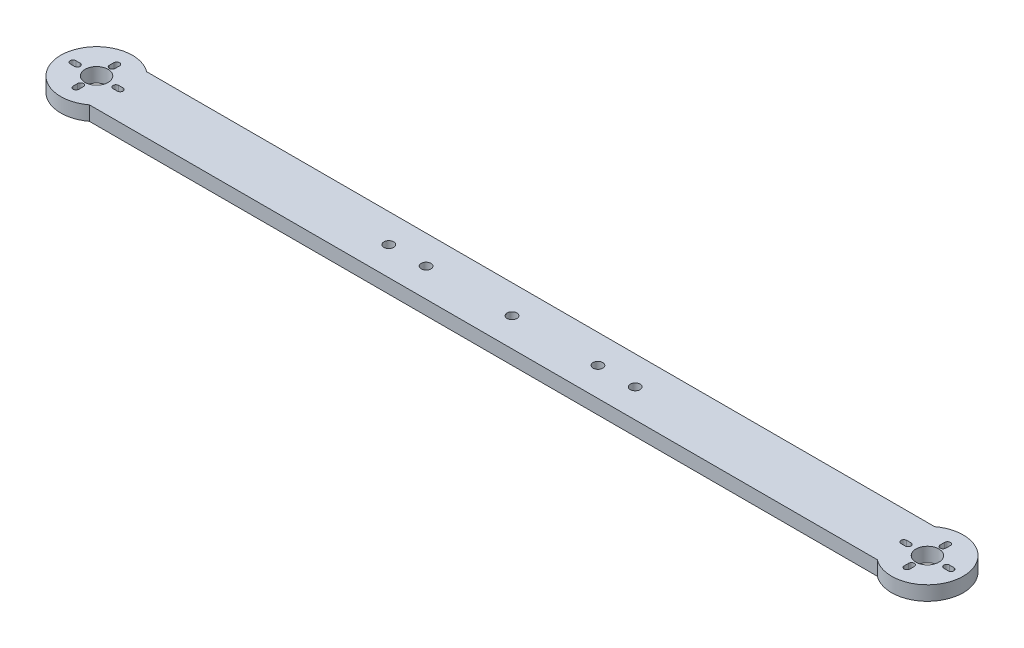
SolidWorks part; units mm, degrees
ref_plane "Front Plane" through (0, 0, 0) normal (0, 0, 1) x (1, 0, 0)
ref_plane "Top Plane" through (0, 0, 0) normal (0, 1, 0) x (1, 0, 0)
ref_plane "Right Plane" through (0, 0, 0) normal (1, 0, 0) x (0, 0, -1)
sketch "Sketch1" plane through (0, 0, 0) normal (0, 1, 0) x (1, 0, 0)
  line L0 (0, 12.7) -> (0, -12.7) construction
  line L1 (-174.625, 12.7) -> (174.625, 12.7)
  line L3 (-174.625, -12.7) -> (174.625, -12.7)
  arc A0 (-174.625, 12.7) -> (-174.625, -12.7) centre (-184.15, 0) ccw
  arc A1 (174.625, -12.7) -> (174.625, 12.7) centre (184.15, 0) ccw
  point P8 (0, 12.7)
  point P12 (0, 0)
  dimension "D3" = 31.75
  dimension "D4" = 31.75
extrude "Boss-Extrude1" add sketch "Sketch1" along normal blind 6.35
sketch "Sketch2" plane through (0, 6.35, 0) normal (0, 1, 0) x (1, 0, 0)
  line L0 (173.6914, 0) -> (175.6086, 0) construction
  line L1 (173.6914, 1.25) -> (175.6086, 1.25)
  line L2 (173.6914, -1.25) -> (175.6086, -1.25)
  line L3 (184.15, 0) -> (184.15, 3.2374) construction
  line L4 (194.6086, 0) -> (192.6914, 0) construction
  line L5 (194.6086, 1.25) -> (192.6914, 1.25)
  line L6 (194.6086, -1.25) -> (192.6914, -1.25)
  line L7 (184.15, 8.9209) -> (184.15, 6.921) construction
  line L8 (185.4, 8.9209) -> (185.4, 6.921)
  line L9 (182.9, 8.9209) -> (182.9, 6.921)
  line L10 (184.1914, -9.079) -> (184.1914, -7.079) construction
  line L11 (185.4414, -9.079) -> (185.4414, -7.079)
  line L12 (182.9414, -9.079) -> (182.9414, -7.079)
  line L13 (0, 0) -> (184.15, 0) construction
  line L14 (0, 0) -> (0, 12.7) construction
  line L15 (174.625, 12.7) -> (-174.625, 12.7) construction
  line L16 (-184.15, 0) -> (-184.15, 3.2374) construction
  line L17 (-184.1914, -9.079) -> (-184.1914, -7.079) construction
  line L18 (-185.4414, -9.079) -> (-185.4414, -7.079)
  line L19 (-182.9414, -9.079) -> (-182.9414, -7.079)
  line L20 (-184.15, 8.9209) -> (-184.15, 6.921) construction
  line L21 (-185.4, 8.9209) -> (-185.4, 6.921)
  line L22 (-182.9, 8.9209) -> (-182.9, 6.921)
  line L23 (-194.6086, 0) -> (-192.6914, 0) construction
  line L24 (-194.6086, 1.25) -> (-192.6914, 1.25)
  line L25 (-194.6086, -1.25) -> (-192.6914, -1.25)
  line L26 (-173.6914, 0) -> (-175.6086, 0) construction
  line L27 (-173.6914, 1.25) -> (-175.6086, 1.25)
  line L28 (-173.6914, -1.25) -> (-175.6086, -1.25)
  circle A0 centre (184.15, 0) radius 5.08
  arc A1 (173.6914, 1.25) -> (173.6914, -1.25) centre (173.6914, 0) ccw
  arc A2 (175.6086, -1.25) -> (175.6086, 1.25) centre (175.6086, 0) ccw
  arc A3 (194.6086, 1.25) -> (194.6086, -1.25) centre (194.6086, 0) cw
  arc A4 (192.6914, -1.25) -> (192.6914, 1.25) centre (192.6914, 0) cw
  arc A5 (185.4, 8.9209) -> (182.9, 8.9209) centre (184.15, 8.9209) ccw
  arc A6 (182.9, 6.921) -> (185.4, 6.921) centre (184.15, 6.921) ccw
  arc A7 (185.4414, -9.079) -> (182.9414, -9.079) centre (184.1914, -9.079) cw
  arc A8 (182.9414, -7.079) -> (185.4414, -7.079) centre (184.1914, -7.079) cw
  circle A9 centre (-184.15, 0) radius 5.08
  arc A10 (-185.4414, -9.079) -> (-182.9414, -9.079) centre (-184.1914, -9.079) ccw
  arc A11 (-182.9414, -7.079) -> (-185.4414, -7.079) centre (-184.1914, -7.079) ccw
  arc A12 (-185.4, 8.9209) -> (-182.9, 8.9209) centre (-184.15, 8.9209) cw
  arc A13 (-182.9, 6.921) -> (-185.4, 6.921) centre (-184.15, 6.921) cw
  arc A14 (-194.6086, 1.25) -> (-194.6086, -1.25) centre (-194.6086, 0) ccw
  arc A15 (-192.6914, -1.25) -> (-192.6914, 1.25) centre (-192.6914, 0) ccw
  arc A16 (-173.6914, 1.25) -> (-173.6914, -1.25) centre (-173.6914, 0) cw
  arc A17 (-175.6086, -1.25) -> (-175.6086, 1.25) centre (-175.6086, 0) cw
  point P4 (174.65, 0)
  point P12 (193.65, 0)
  point P19 (184.15, 7.921)
  point P26 (184.1914, -8.079)
  point P41 (-184.1914, -8.079)
  point P48 (-184.15, 7.921)
  point P55 (-193.65, 0)
  point P62 (-174.65, 0)
  dimension "D4" = 10.16
  dimension "D1" = 16
  dimension "D2" = 19
  dimension "D3" = 184.15
  dimension "D5" = 1.9999
extrude "Cut-Extrude1" cut sketch "Sketch2" against normal through all
sketch "Sketch3" plane through (0, 6.35, 0) normal (0, 1, 0) x (1, 0, 0)
  circle A0 centre (0, 0) radius 2.159
  circle A1 centre (38.1, 0) radius 2.159
  circle A2 centre (-38.1, 0) radius 2.159
  dimension "D1" = 38.1
  dimension "D3" = 4.318
  dimension "D4" = 4.318
  dimension "D5" = 4.318
  dimension "D2" = 38.1
extrude "Cut-Extrude2" cut sketch "Sketch3" against normal through all
ref_plane "Plane1" through (-174.625, 0, 12.7) normal (1, 0, 0) x (0, 0, -1)
sketch "Sketch6" plane through (0, 0, 0) normal (0, -1, 0) x (-1, 0, 0)
  circle A0 centre (54.61, 0) radius 2.159
  circle A1 centre (-54.61, 0) radius 2.159
  circle A2 centre (184.15, 0) radius 5.08 construction
  circle A4 centre (-184.15, 0) radius 5.08 construction
  dimension "D1" = 4.318
  dimension "D2" = 4.318
  dimension "D3" = 129.54
  dimension "D4" = 129.54
extrude "Cut-Extrude3" cut sketch "Sketch6" against normal blind 6.35 contours A1 | A0
